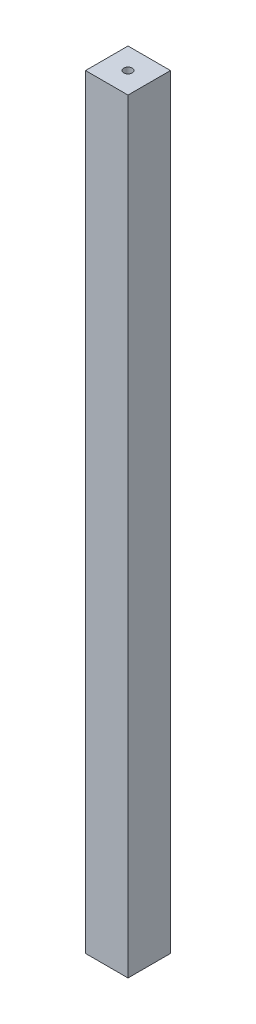
SolidWorks part; units mm, degrees
ref_plane "Спереди" through (0, 0, 0) normal (0, 0, 1) x (1, 0, 0)
ref_plane "Сверху" through (0, 0, 0) normal (0, 1, 0) x (1, 0, 0)
ref_plane "Справа" through (0, 0, 0) normal (1, 0, 0) x (0, 0, -1)
other "Configuration Table"
sketch "Эскиз1" plane through (0, 0, 0) normal (0, 1, 0) x (1, 0, 0)
  line L1 (25, 25) -> (-25, 25)
  line L2 (25, 25) -> (25, -25)
  line L3 (25, -25) -> (-25, -25)
  line L4 (-25, 25) -> (-25, -25)
  line L5 (25, 25) -> (-25, -25) construction
  line L6 (25, -25) -> (-25, 25) construction
  point P0 (0, 0)
extrude "Бобышка-Вытянуть2" add sketch "Эскиз1" along normal blind 900 contours L4 L3 L2 L1
sketch "Эскиз4" plane through (0, 900, 0) normal (0, 1, 0) x (1, 0, 0)
  circle A0 centre (0, 0) radius 5
extrude "Вырез-Вытянуть2" cut sketch "Эскиз4" against normal blind 50
sketch "Эскиз5" plane through (0, 0, 0) normal (0, -1, 0) x (1, 0, 0)
  circle A0 centre (0, 0) radius 5
extrude "Вырез-Вытянуть3" cut sketch "Эскиз5" against normal blind 50
